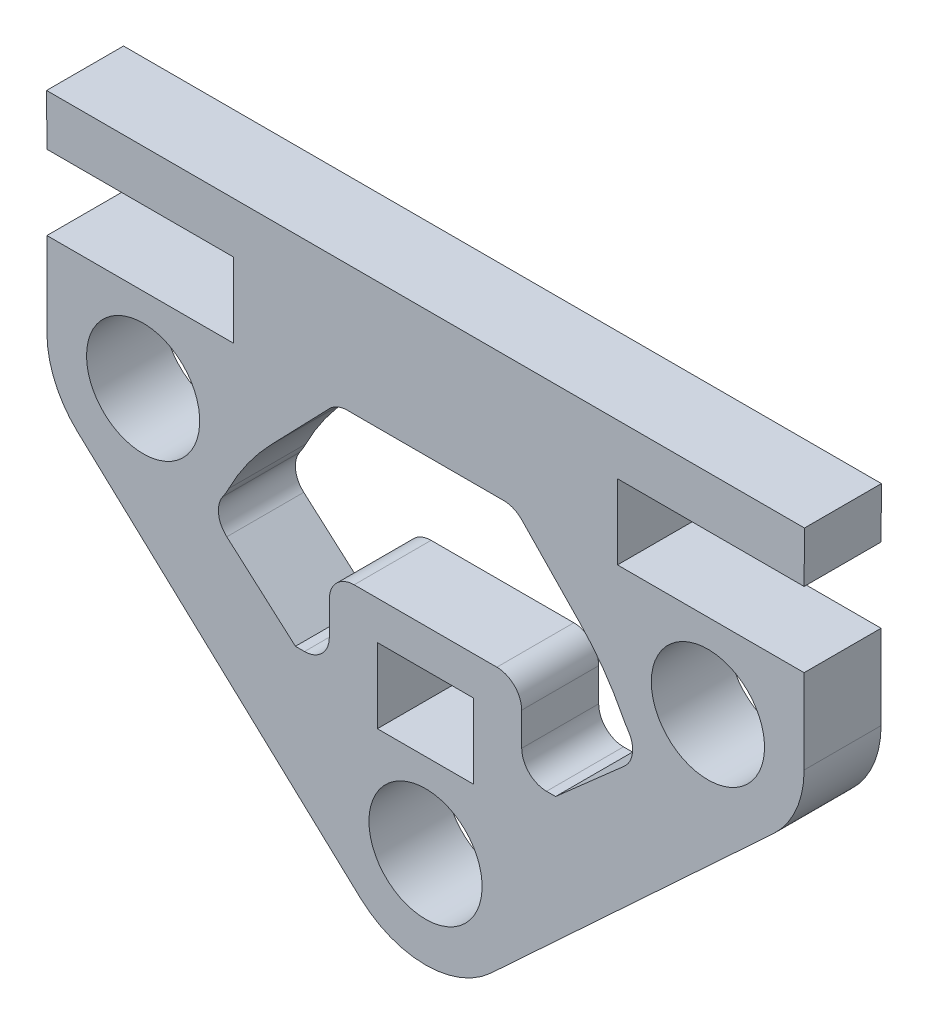
SolidWorks part; units mm, degrees
ref_plane "Front Plane" through (0, 0, 0) normal (0, 0, 1) x (1, 0, 0)
ref_plane "Top Plane" through (0, 0, 0) normal (0, 1, 0) x (1, 0, 0)
ref_plane "Right Plane" through (0, 0, 0) normal (1, 0, 0) x (0, 0, -1)
sketch "Sketch1" plane through (0, 0, 0) normal (0, 0, 1) x (1, 0, 0)
  line L0 (-41.0132, 32.5085) -> (-41.0132, 29.4085) construction
  line L1 (-10.5132, 32.5085) -> (-10.5132, 29.4085) construction
  line L2 (-41.0274, 34.5085) -> (-10.4989, 34.5085)
  line L3 (-33.2632, 29.4085) -> (-41.0132, 29.4085) construction
  line L4 (-41.0132, 32.462) -> (-41.0274, 34.5085)
  line L5 (-33.7675, 22.5686) -> (-31.0029, 20.1301)
  line L6 (-17.7588, 22.5686) -> (-20.5234, 20.1301)
  line L7 (-18.0307, 29.455) -> (-10.5132, 29.455) construction
  line L8 (-33.4957, 32.462) -> (-33.4957, 29.455)
  line L9 (-18.0307, 32.462) -> (-18.0307, 29.455)
  line L10 (-28.9171, 29.4085) -> (-22.6092, 29.4085)
  line L11 (-27.7032, 21.912) -> (-23.8232, 21.912)
  line L12 (-41.0132, 29.455) -> (-41.0132, 26.0585)
  line L13 (-10.4989, 34.5085) -> (-10.5132, 32.462)
  line L14 (-27.7032, 21.912) -> (-27.7032, 18.905)
  line L15 (-11.7531, 23.2174) -> (-23.1281, 12.6674)
  line L16 (-39.7732, 23.2174) -> (-28.3982, 12.6674)
  line L17 (-41.0132, 32.462) -> (-33.4957, 32.462)
  line L18 (-27.7032, 18.905) -> (-23.8232, 18.905)
  line L19 (-41.0132, 29.455) -> (-33.4957, 29.455)
  line L20 (-23.8232, 21.912) -> (-23.8232, 18.905)
  line L21 (-18.0307, 32.462) -> (-10.5132, 32.462)
  line L22 (-27.7632, 18.8585) -> (-23.7632, 21.9585) construction
  line L23 (-18.0307, 29.455) -> (-10.5132, 29.455)
  line L24 (-31.0029, 20.1301) -> (-30.6382, 20.1301)
  line L25 (-28.6382, 23.4585) -> (-22.8892, 23.4585)
  line L26 (-10.5132, 26.0585) -> (-10.5132, 29.455)
  line L27 (-31.9863, 26.6707) -> (-29.6363, 29.1033)
  line L28 (-21.8892, 22.4593) -> (-21.8882, 21.1301)
  line L31 (-21.89, 29.1033) -> (-19.54, 26.6707)
  line L32 (-20.8882, 20.1301) -> (-20.5234, 20.1301)
  line L34 (-29.6382, 21.1301) -> (-29.6382, 22.4585)
  circle A0 centre (-14.3882, 26.0585) radius 2.2795
  circle A1 centre (-37.1382, 26.0585) radius 2.2795
  circle A2 centre (-25.7632, 15.5085) radius 2.2795
  arc A3 (-11.7531, 23.2174) -> (-10.5132, 26.0585) centre (-14.3882, 26.0585) ccw
  arc A4 (-39.7732, 23.2174) -> (-41.0132, 26.0585) centre (-37.1382, 26.0585) cw
  arc A5 (-28.3982, 12.6674) -> (-23.1281, 12.6674) centre (-25.7632, 15.5085) ccw
  arc A6 (-33.9331, 23.8806) -> (-33.6907, 24.2891) centre (-37.1382, 26.0585) ccw
  arc A7 (-17.5932, 23.8806) -> (-17.8356, 24.2891) centre (-14.3882, 26.0585) cw
  arc A8 (-21.8882, 21.1301) -> (-20.8882, 20.1301) centre (-20.8882, 21.1301) ccw
  arc A9 (-33.6907, 24.2891) -> (-31.9863, 26.6707) centre (-24.7942, 19.7228) cw
  arc A10 (-33.9331, 23.8806) -> (-33.7675, 22.5686) centre (-33.106, 23.3185) ccw
  arc A11 (-29.6382, 21.1301) -> (-30.6382, 20.1301) centre (-30.6382, 21.1301) cw
  arc A12 (-28.6382, 23.4585) -> (-29.6382, 22.4585) centre (-28.6382, 22.4585) ccw
  arc A13 (-17.5932, 23.8806) -> (-17.7588, 22.5686) centre (-18.4203, 23.3185) cw
  arc A14 (-17.8356, 24.2891) -> (-19.54, 26.6707) centre (-26.7322, 19.7228) ccw
  arc A15 (-22.8892, 23.4585) -> (-21.8892, 22.4593) centre (-22.8892, 22.4585) cw
  arc A16 (-28.9171, 29.4085) -> (-29.6363, 29.1033) centre (-28.9171, 28.4085) ccw
  arc A17 (-22.6092, 29.4085) -> (-21.89, 29.1033) centre (-22.6092, 28.4085) cw
  point P31 (-33.2632, 26.0585)
  point P43 (-18.2632, 26.0585)
  point P50 (-22.1849, 18.6647)
  point P66 (-21.8882, 20.1301)
  dimension "D6" = 10
  dimension "D9" = 15.5143
  dimension "D11" = 1
  dimension "D12" = 3.875
  dimension "D14" = 1
  dimension "D16" = 1
  dimension "D10" = 5.9017
extrude "Extrude1" add sketch "Sketch1" along normal blind 3.1
